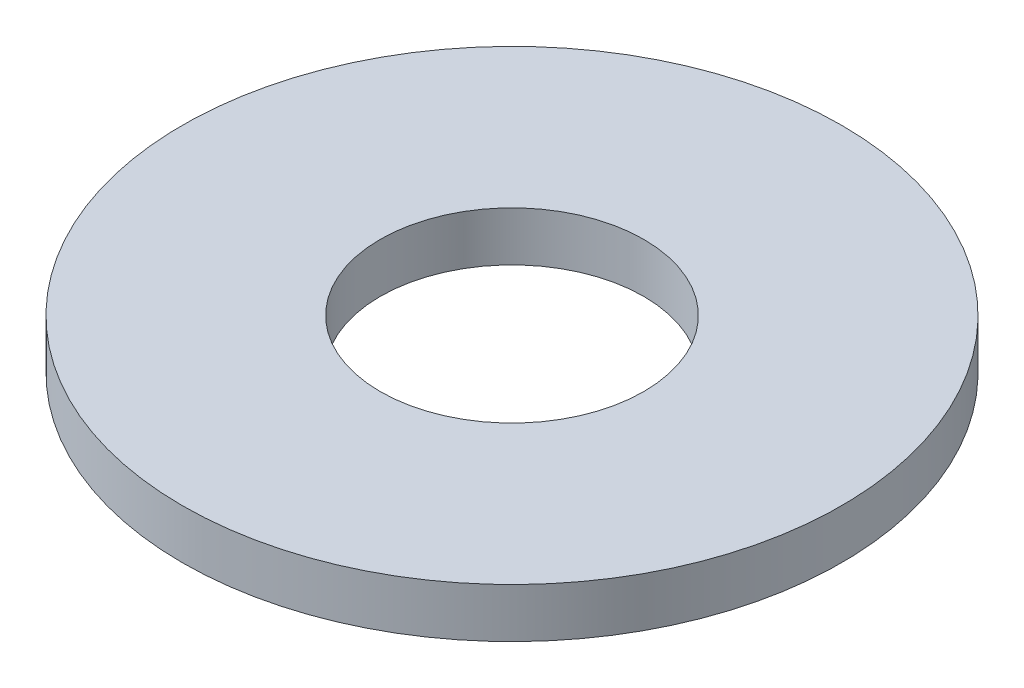
SolidWorks part; units mm, degrees
material "AISI 304"
ref_plane "前视基准面" through (0, 0, 0) normal (0, 0, 1) x (1, 0, 0)
ref_plane "上视基准面" through (0, 0, 0) normal (0, 1, 0) x (1, 0, 0)
ref_plane "右视基准面" through (0, 0, 0) normal (1, 0, 0) x (0, 0, -1)
other "Configuration Table"
sketch "草图1" plane through (0, 0, 0) normal (1, 0, 0) x (0, 0, -1)
  line L0 (0, 0) -> (0, 11030.1797) construction
  line L2 (0.8, 0.15) -> (2, 0.15)
  line L3 (0.8, 0.15) -> (0.8, -0.15)
  line L4 (0.8, -0.15) -> (2, -0.15)
  line L5 (2, 0.15) -> (2, -0.15)
  point P7 (0.8, 0)
  dimension "d1" = 1.6
  dimension "d2" = 4
  dimension "h" = 0.3
revolve "旋转1" add sketch "草图1" angle 360 about L0
